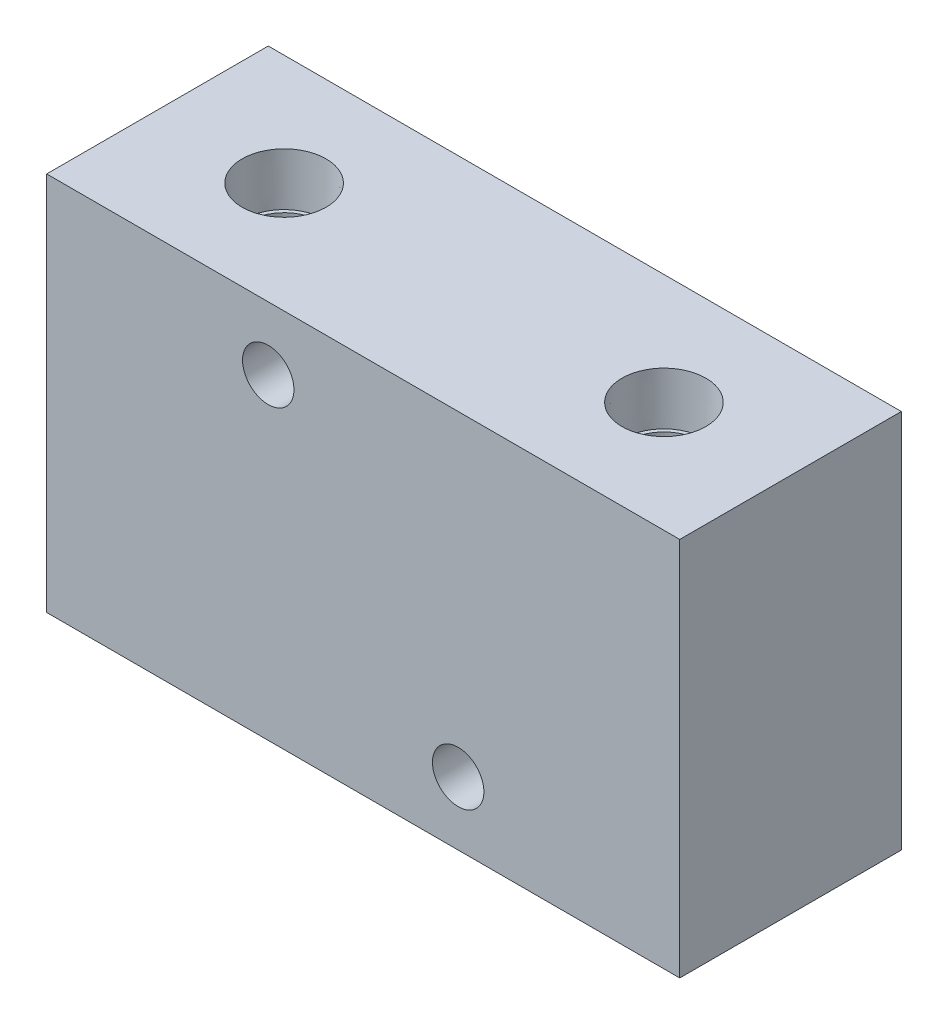
SolidWorks part; units mm, degrees
ref_plane "Front" through (0, 0, 0) normal (0, 0, 1) x (1, 0, 0)
ref_plane "Top" through (0, 0, 0) normal (0, 1, 0) x (1, 0, 0)
ref_plane "Right" through (0, 0, 0) normal (1, 0, 0) x (0, 0, -1)
sketch "Sketch1" plane through (0, 0, 0) normal (0, 0, 1) x (1, 0, 0)
  line L0 (-63.5, -38.1) -> (63.5, -38.1)
  line L1 (-63.5, -38.1) -> (-63.5, 38.1)
  line L2 (63.5, 38.1) -> (-63.5, 38.1)
  line L3 (63.5, 38.1) -> (63.5, -38.1)
  line L4 (-63.5, 38.1) -> (63.5, -38.1) construction
  dimension "D1" = 127
  dimension "D2" = 76.2
extrude "Base-Extrude" add sketch "Sketch1" along normal blind 44.45
sketch "Sketch6" plane through (0, 38.1, 0) normal (0, 1, 0) x (-1, 0, 0)
  line L0 (-63.5, 22.225) -> (63.5, 22.225) construction
  line L1 (-63.5, 44.45) -> (-63.5, 0) construction
  line L2 (63.5, 44.45) -> (63.5, 0) construction
  line L3 (-38.1, 0) -> (-38.1, 22.225) construction
  line L4 (-63.5, 0) -> (63.5, 0) construction
  line L5 (0, 0) -> (0, 22.225) construction
  line L6 (38.1, 0) -> (38.1, 22.225) construction
  dimension "D1" = 38.1
  dimension "D2" = 38.1
sketch "Sketch7" plane through (140.203, -38.1, 6.5132) normal (0, -1, 0) x (1, 0, 0)
  line L0 (-203.703, 15.7118) -> (-76.703, 15.7118) construction
  line L3 (-178.303, -6.5132) -> (-178.303, 15.7118) construction
  line L5 (-140.203, -6.5132) -> (-140.203, 15.7118) construction
  line L6 (-102.103, -6.5132) -> (-102.103, 15.7118) construction
  line L7 (-76.703, 37.9368) -> (-76.703, -6.5132) construction
  line L8 (-203.703, -6.5132) -> (-76.703, -6.5132) construction
sketch "Sketch8" plane through (0, 0, 0) normal (0, 0, -1) x (-1, 0, 0)
  line L0 (0, -38.1) -> (0, 38.1) construction
  point P4 (0, 0)
sketch "Sketch13" plane through (-63.5, 42.3823, -29.0742) normal (-1, 0, 0) x (0, 0, 1)
  line L0 (29.0742, -4.2823) -> (73.2734, -80.4823) construction
  line L1 (73.5242, -80.4823) -> (29.0742, -80.4823) construction
  circle A0 centre (51.1738, -42.3823) radius 10.4724
  dimension "Pipe OD" = 20.9448
extrude "Cut-Extrude7" cut sketch "Sketch13" against normal blind 13.5712 draft 1.783
cosmetic thread "Cosmetic Thread3" parameters "D2"=21.336
sketch "Sketch14" plane through (-63.5, 38.1, -63.5) normal (-1, 0, 0) x (0, 0, 1)
  circle A0 centre (85.5996, -38.1) radius 8.9281
  dimension "D1" = 17.8562
extrude "Cut-Extrude8" cut sketch "Sketch14" against normal blind 114.3
sketch "Sketch15" plane through (50.8, 38.1, -63.5) normal (-1, 0, 0) x (0, 0, 1)
  arc A1 (94.5277, -38.1) -> (94.5277, -38.1) centre (85.5996, -38.1) ccw
  circle A2 centre (85.5996, -38.1) radius 8.9281
  dimension "D1" = 0
extrude "Cut-Extrude9" cut sketch "Sketch15" against normal up to next (12.7 mm away) draft 60
sketch "Sketch16" plane through (-49.9288, 38.1, -63.5) normal (-1, 0, 0) x (0, 0, 1)
  circle A0 centre (85.5996, -38.1) radius 10.0499 construction
  circle A1 centre (85.5996, -38.1) radius 10.0499
other ".50 NPT1"
sketch "Sketch17" plane through (97.8636, -38.1, 25.9971) normal (0, -1, 0) x (1, 0, 0)
  circle A0 centre (-59.7636, -3.7721) radius 8.4188
  dimension "Pipe OD" = 16.8377
extrude "Cut-Extrude10" cut sketch "Sketch17" against normal blind 10.3302 draft 1.783
cosmetic thread "Cosmetic Thread4" parameters "D2"=17.145
sketch "Sketch18" plane through (98.7025, -38.1, 22.225) normal (0, -1, 0) x (1, 0, 0)
  circle A0 centre (-60.6025, 0) radius 7.3406
  dimension "D1" = 14.6812
extrude "Cut-Extrude11" cut sketch "Sketch18" against normal up to surface (38.1 mm away) up to plane "Top"
sketch "Sketch19" [suppressed] plane through (98.7025, -12.7, 22.225) normal (0, -1, 0) x (1, 0, 0)
  circle A1 centre (-60.6025, 0) radius 7.3406
  circle A2 centre (-60.6025, 0) radius 7.3406
  dimension "D1" = 0
extrude "Cut-Extrude12" [suppressed] cut sketch "Sketch19" against normal up to next draft 60
sketch "Sketch20" plane through (98.7025, -27.7698, 22.225) normal (0, -1, 0) x (1, 0, 0)
  circle A1 centre (-60.6025, 0) radius 8.0972
  circle A2 centre (-60.6025, 0) radius 8.0972
  dimension "D1" = 0
other ".38 NPT2" [suppressed]
sketch "Sketch21" plane through (60.496, -38.1, 35.4376) normal (0, -1, 0) x (1, 0, 0)
  circle A0 centre (-60.496, -13.2126) radius 8.4188
  dimension "Pipe OD" = 16.8377
extrude "Cut-Extrude13" cut sketch "Sketch21" against normal blind 10.3302 draft 1.783
cosmetic thread "Cosmetic Thread5" parameters "D2"=17.145
sketch "Sketch22" plane through (61.3349, -38.1, 31.6655) normal (0, -1, 0) x (1, 0, 0)
  circle A0 centre (-61.3349, -9.4405) radius 7.3406
  dimension "D1" = 14.6812
extrude "Cut-Extrude14" cut sketch "Sketch22" against normal up to surface (38.1 mm away) up to plane "Top"
sketch "Sketch23" [suppressed] plane through (61.3349, -12.7, 31.6655) normal (0, -1, 0) x (1, 0, 0)
  circle A1 centre (-61.3349, -9.4405) radius 7.3406
  circle A2 centre (-61.3349, -9.4405) radius 7.3406
  dimension "D1" = 0
extrude "Cut-Extrude15" [suppressed] cut sketch "Sketch23" against normal up to next draft 60
sketch "Sketch24" plane through (61.3349, -27.7698, 31.6655) normal (0, -1, 0) x (1, 0, 0)
  circle A1 centre (-61.3349, -9.4405) radius 8.0972
  circle A2 centre (-61.3349, -9.4405) radius 8.0972
  dimension "D1" = 0
other "LibFeat5" [suppressed]
sketch "Sketch25" plane through (25.3074, -38.1, 36.2367) normal (0, -1, 0) x (1, 0, 0)
  circle A0 centre (-63.4074, -14.0117) radius 8.4188
  dimension "Pipe OD" = 16.8377
extrude "Cut-Extrude16" cut sketch "Sketch25" against normal blind 10.3378 draft 1.783
cosmetic thread "Cosmetic Thread6" parameters "D2"=17.145
sketch "Sketch26" plane through (26.1463, -38.1, 32.4646) normal (0, -1, 0) x (1, 0, 0)
  circle A0 centre (-64.2463, -10.2396) radius 7.3406
  dimension "D1" = 14.6812
extrude "Cut-Extrude17" cut sketch "Sketch26" against normal up to next
sketch "Sketch27" [suppressed] plane through (26.1463, -12.7, 32.4646) normal (0, -1, 0) x (1, 0, 0)
  circle A1 centre (-64.2463, -10.2396) radius 7.3406
  circle A2 centre (-64.2463, -10.2396) radius 7.3406
  dimension "D1" = 0
extrude "Cut-Extrude18" [suppressed] cut sketch "Sketch27" against normal up to next draft 60
sketch "Sketch28" plane through (26.1463, -27.7622, 32.4646) normal (0, -1, 0) x (1, 0, 0)
  circle A1 centre (-64.2463, -10.2396) radius 8.097
  circle A2 centre (-64.2463, -10.2396) radius 8.097
  dimension "D1" = 0
other "LibFeat6" [suppressed]
mirror "Mirror1" about plane through (0, 0, 0) normal (0, 1, 0) of "Cut-Extrude10", "Cut-Extrude11", "Cut-Extrude16", "Cut-Extrude17"
sketch "Sketch29" plane through (0, 0, 0) normal (0, 0, -1) x (-1, 0, 0)
  line L0 (50, 0) -> (-50, 0) construction
  line L1 (0, -38.1) -> (0, 38.1) construction
  circle A0 centre (-19.05, -25.4) radius 5.1562
  circle A1 centre (19.05, 25.4) radius 5.1562
  dimension "D1" = 10.3124
  dimension "D2" = 25.4
  dimension "D5" = 19.05
  dimension "D3" = 25.4
  dimension "D4" = 19.05
extrude "Cut-Extrude19" cut sketch "Sketch29" against normal through all
